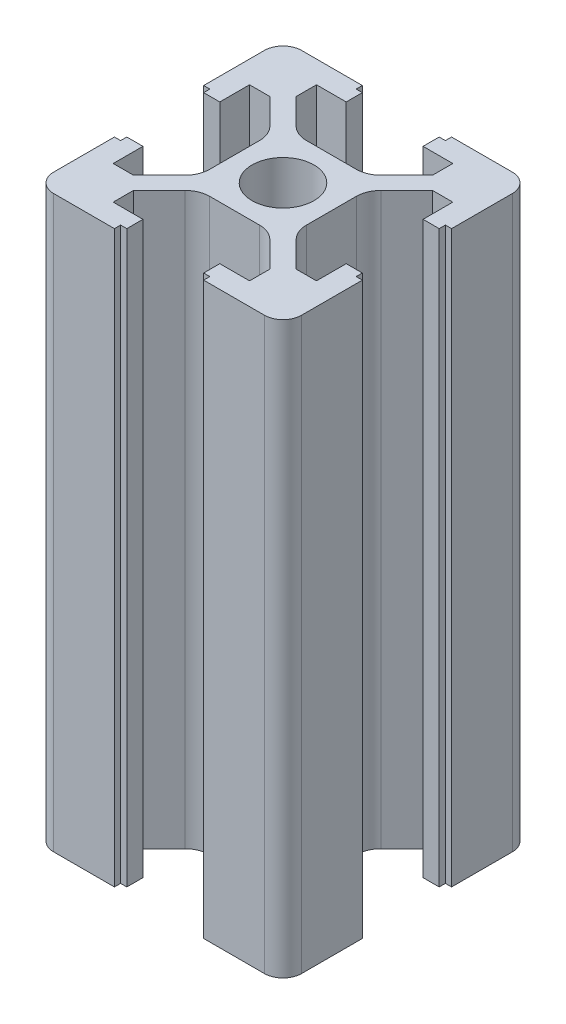
SolidWorks part; units mm, degrees
material "1060 Alloy"
ref_plane "Front Plane" through (0, 0, 0) normal (0, 0, 1) x (1, 0, 0)
ref_plane "Top Plane" through (0, 0, 0) normal (0, 1, 0) x (1, 0, 0)
ref_plane "Right Plane" through (0, 0, 0) normal (1, 0, 0) x (0, 0, -1)
sketch "Sketch1" plane through (0, 0, 0) normal (0, 1, 0) x (1, 0, 0)
  line L1 (8.5, 10) -> (-8.5, 10)
  line L2 (10, 8.5) -> (10, -8.5)
  line L3 (8.5, -10) -> (-8.5, -10)
  line L4 (-10, 8.5) -> (-10, -8.5)
  line L5 (10, 10) -> (-10, -10) construction
  line L6 (10, -10) -> (-10, 10) construction
  arc A0 (-8.5, -10) -> (-10, -8.5) centre (-8.5, -8.5) cw
  arc A1 (10, -8.5) -> (8.5, -10) centre (8.5, -8.5) cw
  arc A2 (8.5, 10) -> (10, 8.5) centre (8.5, 8.5) cw
  arc A3 (-8.5, 10) -> (-10, 8.5) centre (-8.5, 8.5) ccw
  point P0 (0, 0)
  dimension "D3" = 1.5
  dimension "D1" = 20
  dimension "D2" = 20
extrude "Boss-Extrude1" add sketch "Sketch1" along normal blind 46
sketch "Sketch4" plane through (0, 0, 0) normal (0, 1, 0) x (1, 0, 0)
  circle A0 centre (0, 0) radius 2.5
  dimension "D1" = 5
extrude "Cut-Extrude2" cut sketch "Sketch4" along normal through all
sketch "Sketch2" plane through (0, 0, 0) normal (0, -1, 0) x (1, 0, 0)
  line L0 (-3.6, -10) -> (-3.6, -9.5)
  line L1 (8.5, -10) -> (-8.5, -10) construction
  line L2 (-3.6, -9.5) -> (-3.1, -9.5)
  line L3 (-3.1, -9.5) -> (-3.1, -8.2)
  line L4 (-3.1, -8.2) -> (-5.5, -8.2)
  line L5 (-5.5, -8.2) -> (-5.5, -6.5607)
  line L6 (-5.5, -6.5607) -> (-2.8393, -3.9)
  line L7 (-2.8393, -3.9) -> (2.8393, -3.9)
  line L8 (2.8393, -3.9) -> (5.5, -6.5607)
  line L9 (5.5, -6.5607) -> (5.5, -8.2)
  line L10 (5.5, -8.2) -> (3.1, -8.2)
  line L11 (3.1, -8.2) -> (3.1, -9.5)
  line L12 (3.1, -9.5) -> (3.6, -9.5)
  line L13 (3.6, -9.5) -> (3.6, -10)
  line L14 (-5.5, -6.5607) -> (5.5, -6.5607) construction
  line L15 (-3.1, -8.2) -> (3.1, -8.2) construction
  line L16 (3.1, -9.5) -> (-3.1, -9.5) construction
  line L17 (-3.6, -10) -> (3.6, -10)
  line L18 (-9.5607, -9.5607) -> (9.5607, 9.5607) construction
  line L19 (9.5607, -9.5607) -> (-9.5607, 9.5607) construction
  arc A0 (-10, -8.5) -> (-8.5, -10) centre (-8.5, -8.5) ccw construction
  arc A1 (10, 8.5) -> (8.5, 10) centre (8.5, 8.5) ccw construction
  arc A2 (8.5, -10) -> (10, -8.5) centre (8.5, -8.5) ccw construction
  arc A3 (-8.5, 10) -> (-10, 8.5) centre (-8.5, 8.5) ccw construction
  point P5 (0, -3.9)
  point P17 (0, -9.5)
  point P18 (0, -8.2)
  point P20 (0, -6.5607)
  point P21 (0, -10)
  dimension "D1" = 7.2
  dimension "D2" = 6.2
  dimension "D3" = 0.5
  dimension "D4" = 11
  dimension "D5" = 6.1
  dimension "D6" = 1.8
  dimension "D7" = 0.75
extrude "Cut-Extrude1" cut sketch "Sketch2" against normal through all
fillet "Fillet1" radius 2 2 edges at (2.8393, 23, -3.9) (-2.8393, 23, -3.9)
pattern_circular "CirPattern1" count 4 over 360 about axis through (0, 0, 0) along (0, 1, 0) of "Cut-Extrude1", "Fillet1"
